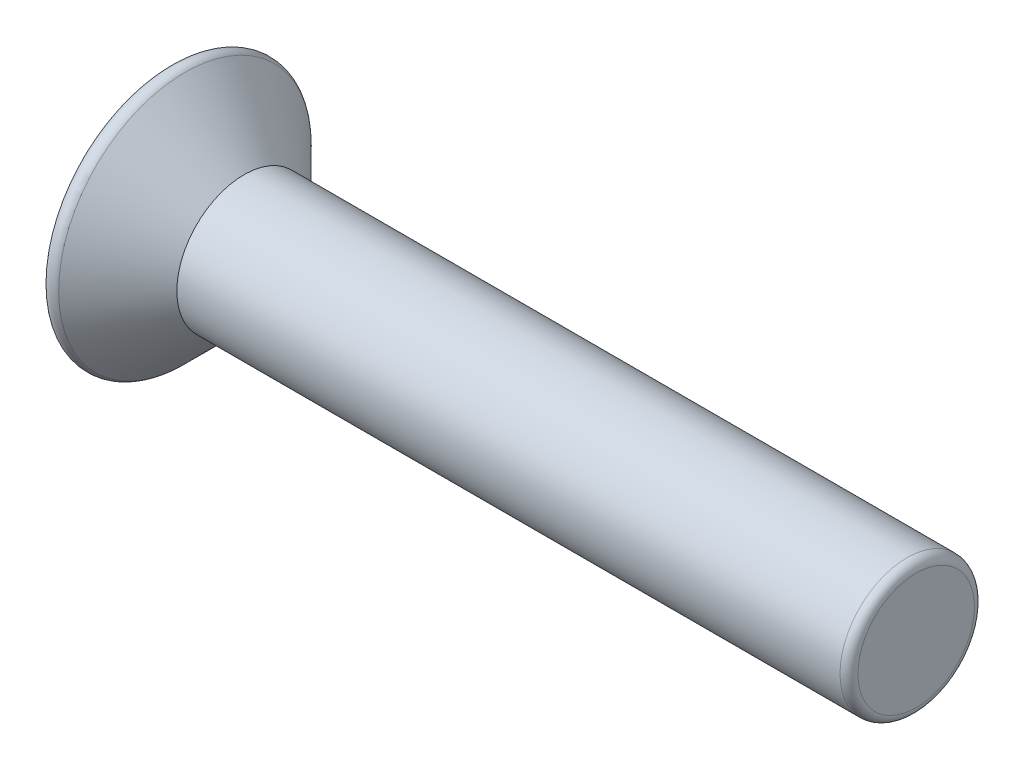
SolidWorks part; units mm, degrees
ref_plane "Plan de face" through (0, 0, 0) normal (0, 0, 1) x (1, 0, 0)
ref_plane "Plan de dessus" through (0, 0, 0) normal (0, 1, 0) x (1, 0, 0)
ref_plane "Plan de droite" through (0, 0, 0) normal (1, 0, 0) x (0, 0, -1)
sketch "Esquisse1" plane through (0, 0, 0) normal (0, 0, 1) x (1, 0, 0)
  line L0 (-5.7689, 0) -> (8.695, 0) construction
  line L1 (0, 0) -> (0, 3.16)
  line L2 (0, 3.16) -> (1.66, 1.5)
  line L3 (1.66, 1.5) -> (16.66, 1.5)
  line L4 (16.66, 1.5) -> (16.66, 0)
  line L5 (0, 0) -> (16.66, 0)
  dimension "D1" = 3.16
  dimension "D2" = 45
  dimension "D3" = 1.66
  dimension "D4" = 15
revolve "Révolution1" add sketch "Esquisse1" angle 360 about L0
sketch "Esquisse2" plane through (0, 0, 0) normal (-1, 0, 0) x (0, 0, 1)
  line L1 (0, -1.1) -> (0.9526, -0.55)
  line L2 (0.9526, -0.55) -> (0.9526, 0.55)
  line L3 (0.9526, 0.55) -> (0, 1.1)
  line L4 (0, 1.1) -> (-0.9526, 0.55)
  line L5 (-0.9526, 0.55) -> (-0.9526, -0.55)
  line L6 (-0.9526, -0.55) -> (0, -1.1)
  circle A0 centre (0, 0) radius 0.9526 construction
  dimension "D1" = 2.2
extrude "Enlèv. mat.-Extru.1" cut sketch "Esquisse2" against normal blind 0.1
fillet "Congé1" radius 0.2 2 edges at (16.66, 0, 1.5) (0, 0, 3.16)
